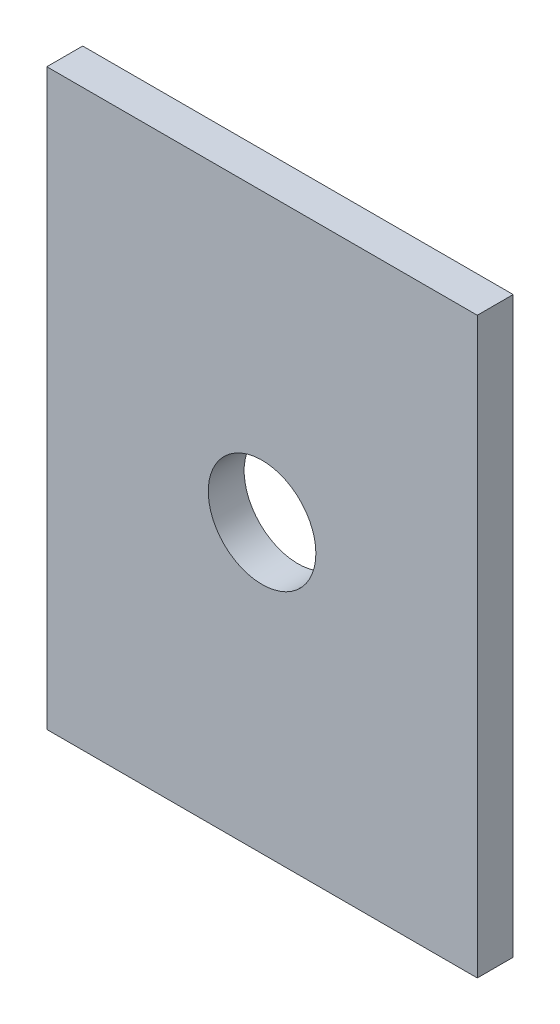
SolidWorks part; units mm, degrees
ref_plane "Front Plane" through (0, 0, 0) normal (0, 0, 1) x (1, 0, 0)
ref_plane "Top Plane" through (0, 0, 0) normal (0, 1, 0) x (1, 0, 0)
ref_plane "Right Plane" through (0, 0, 0) normal (1, 0, 0) x (0, 0, -1)
sketch "Sketch1" plane through (0, 0, 0) normal (0, 0, 1) x (1, 0, 0)
  line L1 (-19.05, 25.4) -> (19.05, 25.4)
  line L2 (-19.05, 25.4) -> (-19.05, -25.4)
  line L3 (-19.05, -25.4) -> (19.05, -25.4)
  line L4 (19.05, 25.4) -> (19.05, -25.4)
  line L5 (-19.05, 25.4) -> (19.05, -25.4) construction
  line L6 (-19.05, -25.4) -> (19.05, 25.4) construction
  circle A0 centre (0, 0) radius 4.7625
  point P0 (0, 0)
  dimension "D3" = 9.525
  dimension "D1" = 50.8
  dimension "D2" = 38.1
extrude "Boss-Extrude1" add sketch "Sketch1" along normal blind 3.175
